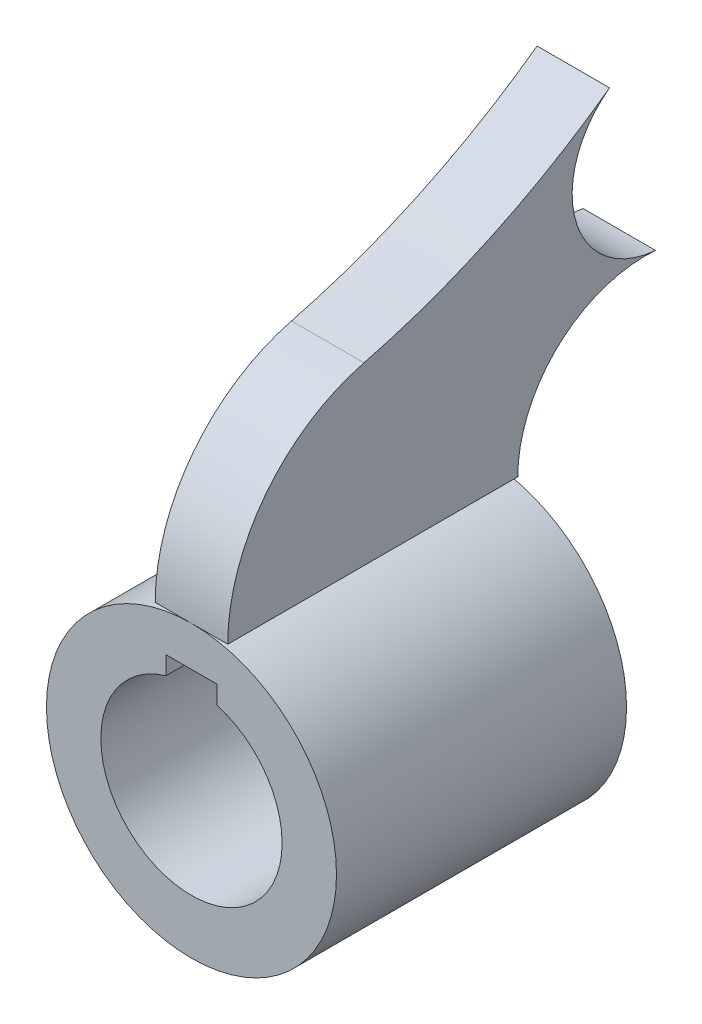
SolidWorks part; units mm, degrees
ref_plane "Front Plane" through (0, 0, 0) normal (0, 0, 1) x (1, 0, 0)
ref_plane "Top Plane" through (0, 0, 0) normal (0, 1, 0) x (1, 0, 0)
ref_plane "Right Plane" through (0, 0, 0) normal (1, 0, 0) x (0, 0, -1)
sketch "Sketch1" plane through (0, 0, 0) normal (0, 0, 1) x (1, 0, 0)
  line L0 (0, 0) -> (0, 46.1793) construction
  line L1 (-7, 29) -> (7, 29)
  line L2 (-7, 29) -> (-7, 24)
  line L3 (7, 29) -> (7, 24)
  arc A0 (-7, 24) -> (7, 24) centre (0, 0) ccw
  circle A1 centre (0, 0) radius 40
  point P7 (0, 29)
  dimension "D1" = 50
  dimension "D2" = 80
  dimension "D3" = 29
  dimension "D4" = 14
extrude "Boss-Extrude1" add sketch "Sketch1" against normal blind 80
sketch "Sketch2" plane through (0, 0, 0) normal (1, 0, 0) x (0, 0, -1)
  line L0 (80, -40) -> (80, 40) construction
  line L1 (0, 40) -> (0, 0) construction
  line L2 (80, 40) -> (0, 40) construction
  line L3 (0, 40) -> (0, -40) construction
  line L4 (80, 40) -> (80, 10.1156) construction
  line L5 (0, 40) -> (80, 40)
  circle A0 centre (120, 100) radius 15
  circle A1 centre (120, 100) radius 25
  arc A2 (0, 40) -> (37.5909, 88.4357) centre (50, 40) cw
  arc A3 (37.5909, 88.4357) -> (105.3283, 120.242) centre (-12.0457, 282.1783) ccw
  arc A4 (80, 40) -> (119.9814, 74.8649) centre (115.1923, 40) cw
  dimension "D3" = 30
  dimension "D4" = 50
  dimension "D5" = 50
  dimension "D6" = 200
  dimension "D1" = 100
  dimension "D2" = 40
extrude "Boss-Extrude2" add sketch "Sketch2" along normal mid plane 20 separate body contours L5 A4 A1 A3 A2
